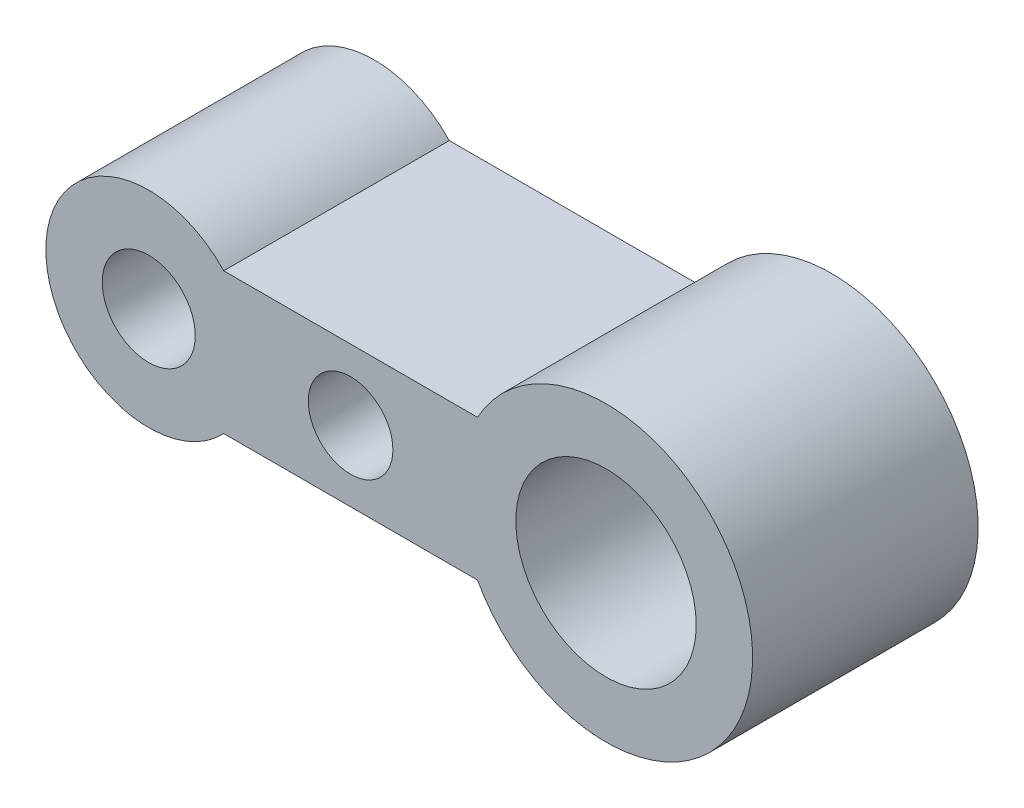
SolidWorks part; units mm, degrees
ref_plane "Alzado" through (0, 0, 0) normal (0, 0, 1) x (1, 0, 0)
ref_plane "Planta" through (0, 0, 0) normal (0, 1, 0) x (1, 0, 0)
ref_plane "Vista lateral" through (0, 0, 0) normal (1, 0, 0) x (0, 0, -1)
sketch "Croquis1" plane through (0, 0, 0) normal (0, 0, 1) x (1, 0, 0)
  line L0 (2.6594, 2.5) -> (11.6594, 2.5)
  line L1 (0, 0) -> (21.7907, 0) construction
  line L2 (2.6594, -2.5) -> (11.6594, -2.5)
  circle A0 centre (0, 0) radius 1.65
  circle A1 centre (0, 0) radius 3.65
  circle A5 centre (16.219, 0) radius 3.2
  circle A6 centre (16.219, 0) radius 5.2
  dimension "D1" = 3.3
  dimension "D4" = 6.4
  dimension "D5" = 2
  dimension "D3" = 9
  dimension "D6" = 2.5
  dimension "D2" = 2
extrude "Saliente-Extruir1" add sketch "Croquis1" along normal blind 8
sketch "Croquis3" plane through (0, 0, 0) normal (0, 0, -1) x (-1, 0, 0)
  line L0 (-7.1594, 2.5) -> (-7.1594, -2.5) construction
  line L3 (-2.6594, -2.5) -> (-11.6594, -2.5) construction
  line L4 (-2.6594, 2.5) -> (-11.6594, 2.5) construction
  circle A0 centre (-7.1594, 0) radius 1.5
  point P2 (0, 0)
  point P5 (-7.1594, -2.5)
  point P8 (-7.873, 2.75)
  point P9 (0, 0)
  point P10 (0, 0)
  point P11 (-7.1594, 2.5)
  dimension "D1" = 3
extrude "Cortar-Extruir1" cut sketch "Croquis3" against normal blind 21.5
